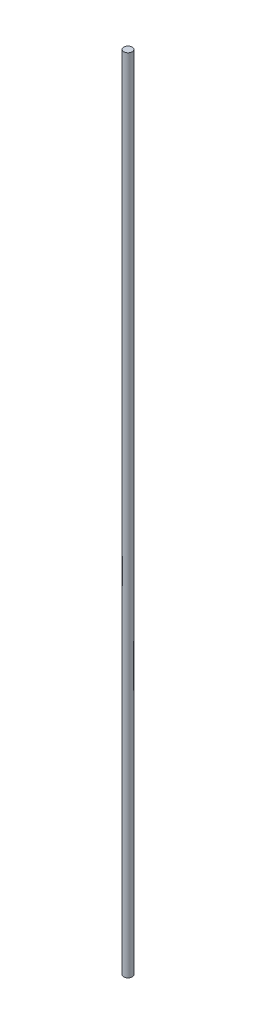
SolidWorks part; units mm, degrees
material "Stainless Steel (ferritic)"
ref_plane "Front Plane" through (0, 0, 0) normal (0, 0, 1) x (1, 0, 0)
ref_plane "Top Plane" through (0, 0, 0) normal (0, 1, 0) x (1, 0, 0)
ref_plane "Right Plane" through (0, 0, 0) normal (1, 0, 0) x (0, 0, -1)
sketch "Sketch1" plane through (0, 0, 0) normal (0, 1, 0) x (1, 0, 0)
  circle A0 centre (0, 0) radius 4.7625
  dimension "D1" = 9.525
extrude "Boss-Extrude1" add sketch "Sketch1" along normal mid plane 914.4
